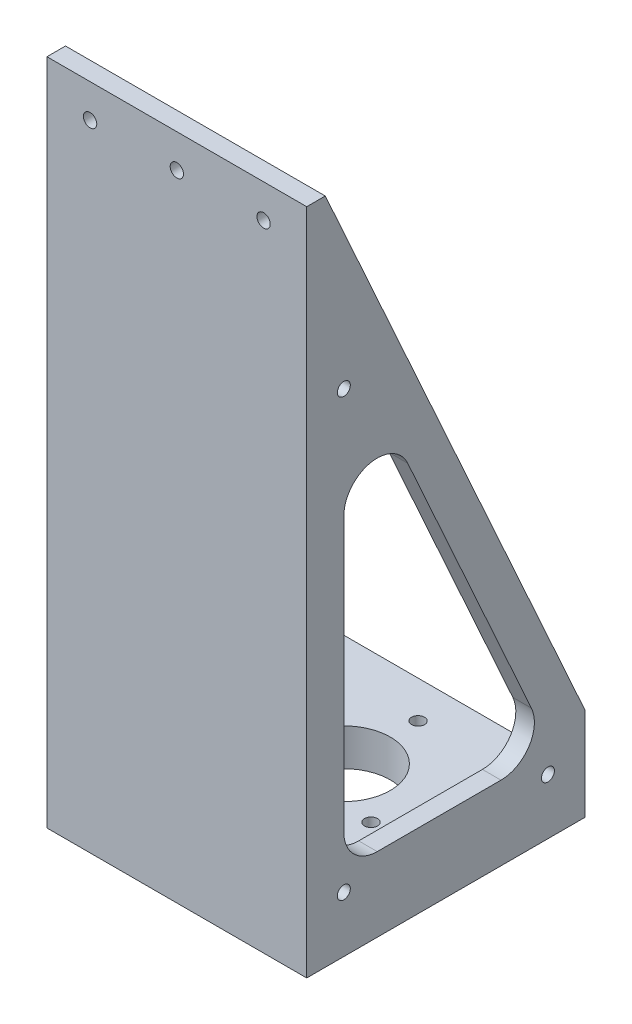
SolidWorks part; units mm, degrees
ref_plane "前视基准面" through (0, 0, 0) normal (0, 0, 1) x (1, 0, 0)
ref_plane "上视基准面" through (0, 0, 0) normal (0, 1, 0) x (1, 0, 0)
ref_plane "右视基准面" through (0, 0, 0) normal (1, 0, 0) x (0, 0, -1)
sketch "草图1" plane through (0, 0, 0) normal (0, 1, 0) x (1, 0, 0)
  line L9 (-35, -45) -> (35, -45)
  line L10 (-35, -45) -> (-35, 30)
  line L11 (-35, 30) -> (35, 30)
  line L12 (35, -45) -> (35, 30)
  circle A0 centre (0, 0) radius 12.5
  circle A1 centre (0, 0) radius 20 construction
  circle A2 centre (0, 20) radius 1.75
  circle A3 centre (17.3205, -10) radius 1.75
  circle A4 centre (-17.3205, -10) radius 1.75
  point P12 (0, 0)
  dimension "D1" = 25
  dimension "D2" = 40
  dimension "D3" = 3.5
  dimension "D5" = 35
  dimension "D6" = 35
  dimension "D7" = 30
  dimension "D8" = 45
  dimension "D4" = 3
extrude "凸台-拉伸1" add sketch "草图1" along normal blind 10
sketch "草图6" plane through (-35, 0, 0) normal (-1, 0, 0) x (0, 0, 1)
  line L0 (40, 180) -> (-30, 25)
  line L1 (45, 0) -> (-30, 0)
  line L2 (45, 0) -> (45, 180)
  line L3 (45, 180) -> (40, 180)
  line L4 (-30, 0) -> (-30, 25)
  line L5 (-30, 10) -> (45, 10) construction
  dimension "D1" = 75
  dimension "D2" = 180
  dimension "D3" = 5
  dimension "D4" = 15
extrude "凸台-拉伸3" add sketch "草图6" against normal blind 5
sketch "草图7" plane through (0, 0, 45) normal (0, 0, 1) x (1, 0, 0)
  line L0 (35, 10) -> (35, 0) construction
  line L1 (-35, 0) -> (35, 0)
  line L2 (-35, 0) -> (-35, 180)
  line L3 (-35, 180) -> (35, 180)
  line L4 (35, 0) -> (35, 180)
  dimension "D1" = 180
sketch "草图8" plane through (35, 0, 0) normal (1, 0, 0) x (0, 0, -1)
  line L2 (-45, 0) -> (-45, 180)
  line L6 (-45, 0) -> (30, 0)
  line L7 (30, 0) -> (30, 25)
  line L8 (-40, 180) -> (30, 25)
  line L9 (-45, 180) -> (-40, 180)
  line L12 (-45, 0) -> (-45, 180) construction
  line L13 (-45, 0) -> (30, 0) construction
  point P1 (0, 0)
  point P3 (0, 0)
  point P8 (0, 0)
  dimension "D1" = 180
  dimension "D2" = 75
  dimension "D3" = 25
  dimension "D4" = 5
extrude "凸台-拉伸4" add sketch "草图8" against normal blind 5
extrude "凸台-拉伸5" add sketch "草图7" against normal blind 5
sketch "草图10" plane through (0, 0, 40) normal (0, 0, -1) x (-1, 0, 0)
  line L0 (-30, 180) -> (30, 180) construction
  line L1 (35, 180) -> (35, 25) construction
  line L2 (-35, 25) -> (-35, 180) construction
  circle A0 centre (-23.375, 171) radius 1.8
  circle A1 centre (23.375, 171) radius 1.8
  circle A2 centre (0, 171) radius 1.8
  dimension "D1" = 3.6
  dimension "D2" = 9
  dimension "D3" = 9
  dimension "D4" = 11.625
  dimension "D5" = 11.625
  dimension "D6" = 46.75
  dimension "D7" = 3.6
  dimension "D8" = 9
  dimension "D9" = 35
extrude "切除-拉伸2" cut sketch "草图10" against normal through all
sketch "草图11" plane through (-35, 0, 0) normal (-1, 0, 0) x (0, 0, 1)
  line L0 (35, 102.8372) -> (35, 29)
  line L1 (26, 20) -> (-7.3458, 20)
  line L2 (-15.5482, 32.7043) -> (17.7977, 106.5415)
  line L3 (45, 180) -> (45, 0) construction
  line L4 (40, 180) -> (-30, 25) construction
  line L5 (-30, 0) -> (45, 0) construction
  line L6 (-30, 25) -> (-30, 0) construction
  arc A0 (35, 102.8372) -> (17.7977, 106.5415) centre (26, 102.8372) ccw
  arc A1 (-15.5482, 32.7043) -> (-7.3458, 20) centre (-7.3458, 29) ccw
  arc A2 (26, 20) -> (35, 29) centre (26, 29) ccw
  circle A3 centre (35, 132.4842) radius 1.75
  circle A4 centre (35, 15) radius 1.75
  circle A5 centre (-20, 15) radius 1.75
  dimension "D4" = 18
  dimension "D5" = 3.5
  dimension "D6" = 10
  dimension "D7" = 15
  dimension "D8" = 15
  dimension "D9" = 10
  dimension "D11" = 15
  dimension "D1" = 10
  dimension "D2" = 20
  dimension "D3" = 10
  dimension "D10" = 10
extrude "切除-拉伸3" cut sketch "草图11" against normal through all
